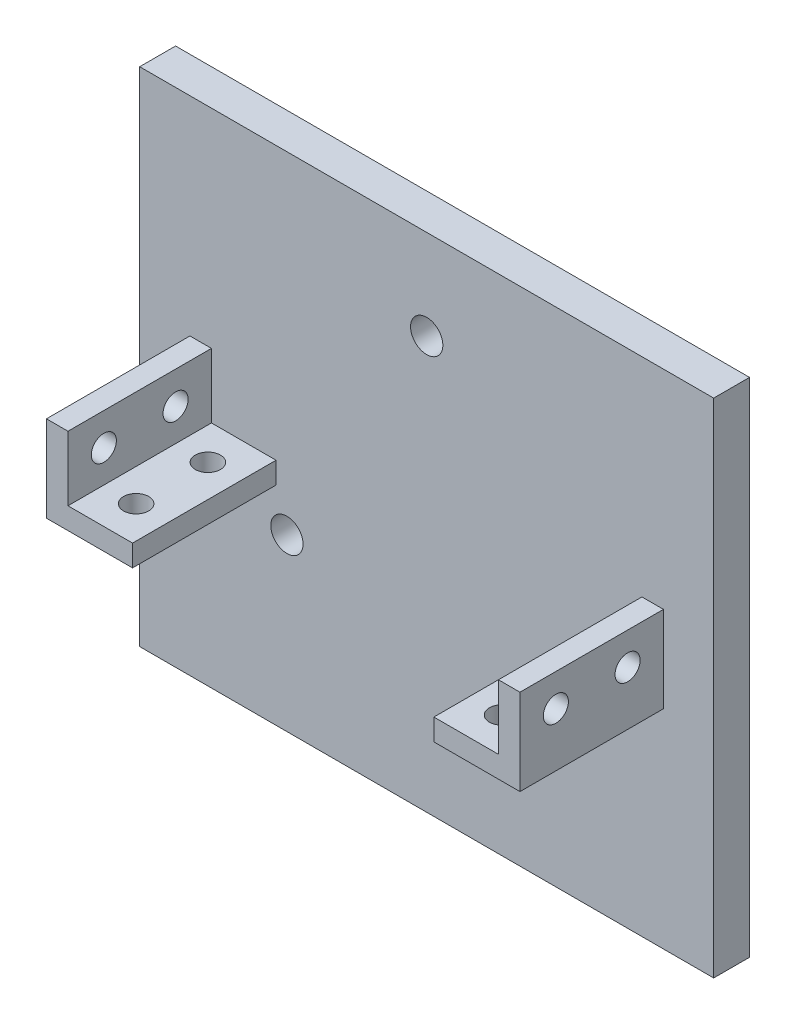
SolidWorks part; units mm, degrees
material "ABS"
ref_plane "正面" through (0, 0, 0) normal (0, 0, 1) x (1, 0, 0)
ref_plane "平面" through (0, 0, 0) normal (0, 1, 0) x (1, 0, 0)
ref_plane "右側面" through (0, 0, 0) normal (1, 0, 0) x (0, 0, -1)
sketch "ｽｹｯﾁ1" plane through (0, 0, 0) normal (0, 0, 1) x (1, 0, 0)
  line L1 (-40, -35) -> (40, -35)
  line L2 (-40, -35) -> (-40, 35)
  line L3 (-40, 35) -> (40, 35)
  line L4 (40, -35) -> (40, 35)
  line L5 (-40, -35) -> (40, 35) construction
  line L6 (-40, 35) -> (40, -35) construction
  point P0 (0, 0)
  dimension "D1" = 70
  dimension "D2" = 80
extrude "ﾎﾞｽ - 押し出し1" add sketch "ｽｹｯﾁ1" along normal blind 5
sketch "ｽｹｯﾁ2" plane through (0, 0, 5) normal (0, 0, 1) x (1, 0, 0)
  line L0 (40, 0) -> (-40, 0) construction
  line L1 (40, -35) -> (40, 35) construction
  line L2 (-40, 35) -> (-40, -35) construction
  line L3 (0, -35) -> (0, 35) construction
  line L4 (-40, -35) -> (40, -35) construction
  line L5 (40, 35) -> (-40, 35) construction
  line L6 (-30, -3) -> (-21, -3)
  line L7 (-21, -3) -> (-21, -6)
  line L8 (-21, -6) -> (-33, -6)
  line L9 (-33, -6) -> (-33, 6)
  line L10 (-33, 6) -> (-30, 6)
  line L11 (-30, 6) -> (-30, -3)
  line L12 (21, -3) -> (21, -6)
  line L13 (21, -6) -> (33, -6)
  line L14 (33, -6) -> (33, 6)
  line L15 (33, 6) -> (30, 6)
  line L16 (30, 6) -> (30, -3)
  line L17 (30, -3) -> (21, -3)
  dimension "D1" = 3
  dimension "D2" = 3
  dimension "D3" = 9
  dimension "D4" = 9
  dimension "D5" = 30
  dimension "D6" = 3
extrude "ﾎﾞｽ - 押し出し2" add sketch "ｽｹｯﾁ2" along normal blind 20
sketch "ｽｹｯﾁ3" plane through (33, 0, 0) normal (1, 0, 0) x (0, 0, -1)
  line L0 (-5, 1.5) -> (-25, 1.5) construction
  line L1 (-5, -35) -> (-5, 35) construction
  line L2 (-25, -6) -> (-25, 6) construction
  line L3 (-25, 6) -> (-5, 6) construction
  circle A0 centre (-10, 1.5) radius 1.75
  circle A1 centre (-20, 1.5) radius 1.75
  dimension "D4" = 3.5
  dimension "D1" = 4.5
  dimension "D2" = 5
  dimension "D3" = 10
extrude "ｶｯﾄ - 押し出し1" cut sketch "ｽｹｯﾁ3" against normal through all
sketch "ｽｹｯﾁ4" plane through (0, -6, 0) normal (0, -1, 0) x (1, 0, 0)
  line L0 (25.5, 25) -> (25.5, 5) construction
  line L1 (21, 25) -> (33, 25) construction
  line L2 (-40, 5) -> (40, 5) construction
  line L3 (-33, 25) -> (-21, 25) construction
  line L4 (-25.5, 25) -> (-25.5, 5) construction
  line L5 (-33, 5) -> (-21, 5) construction
  line L6 (-21, 25) -> (-21, 5) construction
  line L7 (21, 25) -> (21, 5) construction
  line L8 (21, 5) -> (33, 5) construction
  circle A0 centre (25.5, 10) radius 1.75
  circle A1 centre (25.5, 20) radius 1.75
  circle A2 centre (-25.5, 10) radius 1.75
  circle A3 centre (-25.5, 20) radius 1.75
  dimension "D3" = 3.5
  dimension "D1" = 4.5
  dimension "D2" = 4.5
  dimension "D4" = 5
  dimension "D5" = 10
  dimension "D6" = 5
  dimension "D7" = 10
extrude "ｶｯﾄ - 押し出し2" cut sketch "ｽｹｯﾁ4" against normal through all
sketch "ｽｹｯﾁ5" plane through (0, 0, 5) normal (0, 0, 1) x (1, 0, 0)
  circle A0 centre (0, 0) radius 22.5 construction
  circle A1 centre (0, 22.5) radius 2.25
  circle A2 centre (19.4856, -11.25) radius 2.25
  circle A3 centre (-19.4856, -11.25) radius 2.25
  point P11 (0, 0)
  dimension "D1" = 45
  dimension "D2" = 4.5
  dimension "D3" = 3
extrude "ｶｯﾄ - 押し出し3" cut sketch "ｽｹｯﾁ5" against normal through all
